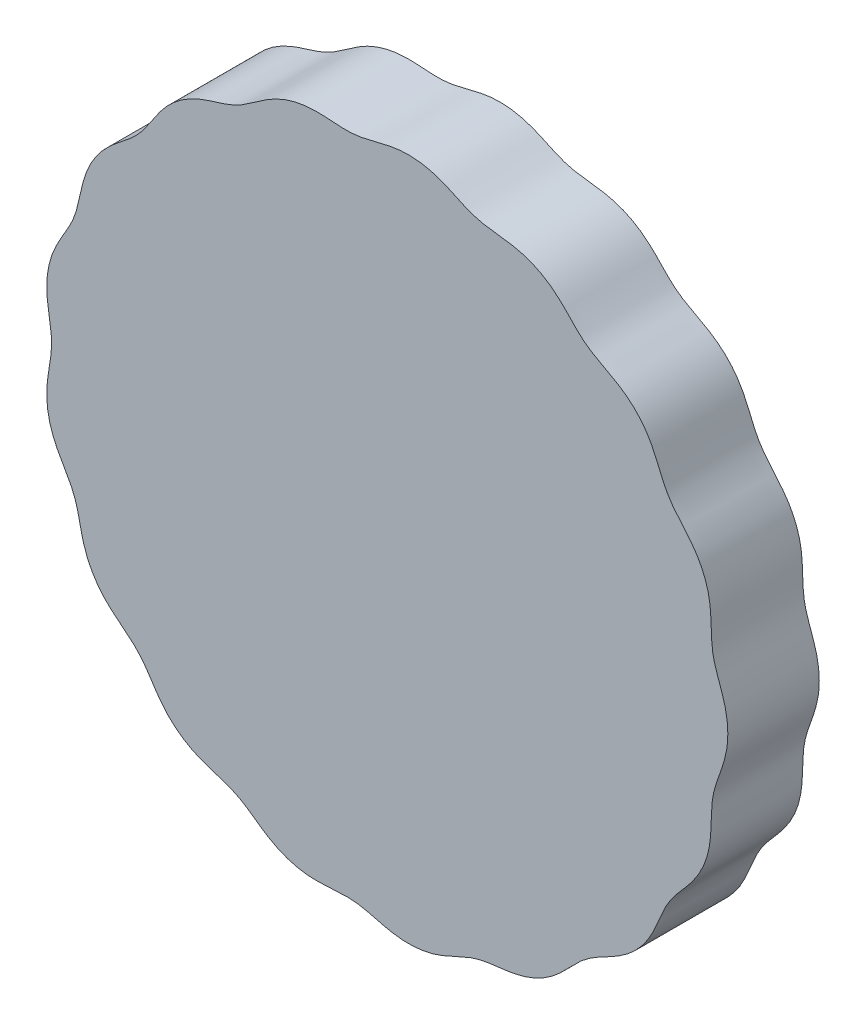
SolidWorks part; units mm, degrees
ref_plane "Front Plane" through (0, 0, 0) normal (0, 0, 1) x (1, 0, 0)
ref_plane "Top Plane" through (0, 0, 0) normal (0, 1, 0) x (1, 0, 0)
ref_plane "Right Plane" through (0, 0, 0) normal (1, 0, 0) x (0, 0, -1)
curve "Curve2"
  spline degree 3 poles (37.4783, -0.2259, 0) (37.4808, 0, 0) (37.4783, 0.2259, 0) (37.4707, 0.4525, 0) (37.4578, 0.6808, 0) (37.4392, 0.9112, 0) (37.4148, 1.1439, 0) (37.3841, 1.3792, 0) (37.347, 1.6168, 0) (37.3035, 1.8564, 0) (37.2536, 2.0975, 0) (37.1976, 2.3394, 0) (37.136, 2.5815, 0) (37.0693, 2.8232, 0) (36.9981, 3.0638, 0) (36.9231, 3.303, 0) (36.8453, 3.5401, 0) (36.7653, 3.7749, 0) (36.6841, 4.007, 0) (36.6025, 4.2364, 0) (36.5213, 4.463, 0) (36.4413, 4.6868, 0) (36.3632, 4.9078, 0) (36.2878, 5.1264, 0) (36.2156, 5.3428, 0) (36.1471, 5.5573, 0) (36.0829, 5.7702, 0) (36.0234, 5.9821, 0) (35.9687, 6.1933, 0) (35.9191, 6.4044, 0) (35.8748, 6.6158, 0) (35.8356, 6.8279, 0) (35.8015, 7.0413, 0) (35.7723, 7.2564, 0) (35.7478, 7.4735, 0) (35.7275, 7.693, 0) (35.7111, 7.9153, 0) (35.6979, 8.1406, 0) (35.6875, 8.369, 0) (35.6793, 8.6006, 0) (35.6724, 8.8355, 0) (35.6662, 9.0736, 0) (35.6601, 9.3147, 0) (35.6531, 9.5586, 0) (35.6447, 9.8048, 0) (35.634, 10.0529, 0) (35.6203, 10.3023, 0) (35.6031, 10.5525, 0) (35.5818, 10.8025, 0) (35.5559, 11.0518, 0) (35.525, 11.2995, 0) (35.4889, 11.5448, 0) (35.4474, 11.787, 0) (35.4005, 12.0254, 0) (35.3483, 12.2596, 0) (35.291, 12.4893, 0) (35.2289, 12.7144, 0) (35.1622, 12.9351, 0) (35.091, 13.152, 0) (35.0154, 13.3656, 0) (34.9354, 13.5768, 0) (34.8506, 13.7862, 0) (34.7607, 13.9947, 0) (34.6651, 14.2029, 0) (34.5635, 14.411, 0) (34.4554, 14.6192, 0) (34.3406, 14.8275, 0) (34.219, 15.0357, 0) (34.0907, 15.2432, 0) (33.956, 15.4497, 0) (33.8155, 15.6548, 0) (33.6697, 15.8579, 0) (33.5194, 16.0587, 0) (33.3655, 16.257, 0) (33.2088, 16.4524, 0) (33.0503, 16.6448, 0) (32.8908, 16.8344, 0) (32.7313, 17.021, 0) (32.5725, 17.205, 0) (32.4153, 17.3865, 0) (32.2603, 17.5659, 0) (32.1082, 17.7436, 0) (31.9595, 17.9199, 0) (31.8147, 18.0955, 0) (31.6742, 18.2708, 0) (31.5382, 18.4462, 0) (31.407, 18.6225, 0) (31.2806, 18.8, 0) (31.1589, 18.9792, 0) (31.042, 19.1607, 0) (30.9296, 19.3449, 0) (30.8215, 19.5321, 0) (30.7173, 19.7227, 0) (30.6165, 19.9169, 0) (30.5188, 20.115, 0) (30.4236, 20.3171, 0) (30.3303, 20.5231, 0) (30.2383, 20.733, 0) (30.1469, 20.9466, 0) (30.0556, 21.1638, 0) (29.9637, 21.3841, 0) (29.8706, 21.6072, 0) (29.7757, 21.8324, 0) (29.6784, 22.0591, 0) (29.5782, 22.2867, 0) (29.4748, 22.5143, 0) (29.3678, 22.7411, 0) (29.2569, 22.9663, 0) (29.1419, 23.1889, 0) (29.0229, 23.408, 0) (28.8999, 23.6228, 0) (28.7731, 23.8327, 0) (28.6426, 24.0371, 0) (28.5088, 24.2356, 0) (28.3719, 24.428, 0) (28.2321, 24.6144, 0) (28.0897, 24.7952, 0) (27.9445, 24.9709, 0) (27.7963, 25.142, 0) (27.6448, 25.3093, 0) (27.4893, 25.4735, 0) (27.3293, 25.635, 0) (27.164, 25.7942, 0) (26.9931, 25.9512, 0) (26.816, 26.1059, 0) (26.6325, 26.2582, 0) (26.4429, 26.4079, 0) (26.2472, 26.5545, 0) (26.0461, 26.6978, 0) (25.8402, 26.8376, 0) (25.6302, 26.9737, 0) (25.417, 27.106, 0) (25.2016, 27.2346, 0) (24.9847, 27.3596, 0) (24.7673, 27.4812, 0) (24.5503, 27.5998, 0) (24.3343, 27.7158, 0) (24.1202, 27.8297, 0) (23.9084, 27.9419, 0) (23.6997, 28.053, 0) (23.4943, 28.1637, 0) (23.2926, 28.2745, 0) (23.0949, 28.3861, 0) (22.9013, 28.4991, 0) (22.7119, 28.614, 0) (22.5265, 28.7314, 0) (22.3452, 28.8518, 0) (22.1677, 28.9756, 0) (21.9937, 29.1033, 0) (21.8229, 29.2352, 0) (21.6549, 29.3715, 0) (21.4892, 29.5124, 0) (21.3254, 29.658, 0) (21.163, 29.8082, 0) (21.0013, 29.963, 0) (20.8399, 30.1221, 0) (20.6781, 30.2853, 0) (20.5156, 30.4522, 0) (20.3517, 30.6222, 0) (20.1861, 30.7949, 0) (20.0183, 30.9695, 0) (19.848, 31.1454, 0) (19.6748, 31.3217, 0) (19.4987, 31.4976, 0) (19.3195, 31.6722, 0) (19.1372, 31.8446, 0) (18.9519, 32.0138, 0) (18.7639, 32.1791, 0) (18.5734, 32.3395, 0) (18.3807, 32.4944, 0) (18.1863, 32.6432, 0) (17.9906, 32.7855, 0) (17.794, 32.921, 0) (17.5967, 33.0498, 0) (17.399, 33.172, 0) (17.2008, 33.2881, 0) (17.0018, 33.3984, 0) (16.8015, 33.5036, 0) (16.5993, 33.6041, 0) (16.3945, 33.7003, 0) (16.1863, 33.7924, 0) (15.974, 33.8804, 0) (15.757, 33.9642, 0) (15.5351, 34.0438, 0) (15.3081, 34.1187, 0) (15.0764, 34.1889, 0) (14.8403, 34.2541, 0) (14.6003, 34.3142, 0) (14.3573, 34.3692, 0) (14.112, 34.4194, 0) (13.8652, 34.465, 0) (13.6178, 34.5064, 0) (13.3705, 34.544, 0) (13.1241, 34.5783, 0) (12.8791, 34.6101, 0) (12.6363, 34.64, 0) (12.3959, 34.6686, 0) (12.1585, 34.6967, 0) (11.9243, 34.725, 0) (11.6934, 34.7542, 0) (11.4659, 34.7851, 0) (11.2418, 34.8181, 0) (11.021, 34.8541, 0) (10.8034, 34.8934, 0) (10.5887, 34.9367, 0) (10.3766, 34.9842, 0) (10.1667, 35.0364, 0) (9.9586, 35.0935, 0) (9.7519, 35.1557, 0) (9.5461, 35.223, 0) (9.3408, 35.2955, 0) (9.1354, 35.3729, 0) (8.9295, 35.4551, 0) (8.7226, 35.5418, 0) (8.5143, 35.6326, 0) (8.3042, 35.7269, 0) (8.092, 35.8243, 0) (7.8773, 35.924, 0) (7.6601, 36.0254, 0) (7.44, 36.1277, 0) (7.2171, 36.2302, 0) (6.9915, 36.3318, 0) (6.7633, 36.4319, 0) (6.5327, 36.5295, 0) (6.3002, 36.6237, 0) (6.066, 36.7138, 0) (5.8308, 36.7991, 0) (5.5952, 36.8788, 0) (5.3596, 36.9526, 0) (5.1248, 37.0199, 0) (4.8911, 37.0807, 0) (4.6591, 37.1349, 0) (4.429, 37.1826, 0) (4.2008, 37.2241, 0) (3.9743, 37.2597, 0) (3.7491, 37.2898, 0) (3.5244, 37.3146, 0) (3.2995, 37.3344, 0) (3.0735, 37.3492, 0) (2.8457, 37.3589, 0) (2.6154, 37.3634, 0) (2.3823, 37.3622, 0) (2.1461, 37.3551, 0) (1.9069, 37.3419, 0) (1.665, 37.3225, 0) (1.4209, 37.2969, 0) (1.1753, 37.2652, 0) (0.9286, 37.2278, 0) (0.6818, 37.1851, 0) (0.4353, 37.1377, 0) (0.1899, 37.0862, 0) (-0.054, 37.0314, 0) (-0.2958, 36.974, 0) (-0.5352, 36.9149, 0) (-0.772, 36.8549, 0) (-1.0059, 36.7949, 0) (-1.237, 36.7355, 0) (-1.4651, 36.6776, 0) (-1.6905, 36.6218, 0) (-1.9134, 36.569, 0) (-2.1339, 36.5195, 0) (-2.3524, 36.474, 0) (-2.5692, 36.4329, 0) (-2.7849, 36.3965, 0) (-2.9998, 36.3651, 0) (-3.2143, 36.3389, 0) (-3.4291, 36.3179, 0) (-3.6444, 36.3021, 0) (-3.8608, 36.2914, 0) (-4.0788, 36.2857, 0) (-4.2986, 36.2845, 0) (-4.5207, 36.2874, 0) (-4.7454, 36.2942, 0) (-4.9729, 36.3041, 0) (-5.2035, 36.3165, 0) (-5.4371, 36.331, 0) (-5.6738, 36.3466, 0) (-5.9136, 36.3627, 0) (-6.1563, 36.3785, 0) (-6.4015, 36.3932, 0) (-6.649, 36.4062, 0) (-6.8982, 36.4165, 0) (-7.1486, 36.4236, 0) (-7.3996, 36.4267, 0) (-7.6504, 36.4253, 0) (-7.9003, 36.4189, 0) (-8.1485, 36.4072, 0) (-8.3943, 36.3899, 0) (-8.637, 36.3669, 0) (-8.8762, 36.3382, 0) (-9.1114, 36.3039, 0) (-9.3424, 36.2644, 0) (-9.5695, 36.2197, 0) (-9.793, 36.1703, 0) (-10.0134, 36.1161, 0) (-10.2316, 36.0573, 0) (-10.4482, 35.9936, 0) (-10.6642, 35.9249, 0) (-10.8802, 35.8507, 0) (-11.0966, 35.7705, 0) (-11.3137, 35.684, 0) (-11.5316, 35.5909, 0) (-11.7499, 35.491, 0) (-11.9684, 35.3844, 0) (-12.1867, 35.2712, 0) (-12.4042, 35.1519, 0) (-12.6204, 35.027, 0) (-12.8348, 34.8971, 0) (-13.0471, 34.7632, 0) (-13.2569, 34.626, 0) (-13.464, 34.4865, 0) (-13.6682, 34.3454, 0) (-13.8697, 34.2038, 0) (-14.0683, 34.0624, 0) (-14.2643, 33.9221, 0) (-14.4578, 33.7837, 0) (-14.6493, 33.6478, 0) (-14.8391, 33.515, 0) (-15.0276, 33.3859, 0) (-15.2152, 33.2608, 0) (-15.4025, 33.1403, 0) (-15.5899, 33.0244, 0) (-15.778, 32.9135, 0) (-15.9673, 32.8074, 0) (-16.1582, 32.7063, 0) (-16.3513, 32.61, 0) (-16.5469, 32.5183, 0) (-16.7454, 32.4309, 0) (-16.9471, 32.3475, 0) (-17.1523, 32.2675, 0) (-17.3611, 32.1906, 0) (-17.5737, 32.116, 0) (-17.7901, 32.0434, 0) (-18.0102, 31.9719, 0) (-18.2339, 31.901, 0) (-18.4609, 31.83, 0) (-18.6908, 31.7582, 0) (-18.9232, 31.685, 0) (-19.1575, 31.6097, 0) (-19.3931, 31.5319, 0) (-19.6292, 31.4509, 0) (-19.8652, 31.3664, 0) (-20.1001, 31.2779, 0) (-20.333, 31.1853, 0) (-20.5632, 31.0883, 0) (-20.7897, 30.9869, 0) (-21.0118, 30.8812, 0) (-21.229, 30.7714, 0) (-21.4406, 30.6575, 0) (-21.6465, 30.54, 0) (-21.8467, 30.419, 0) (-22.0414, 30.2948, 0) (-22.231, 30.1674, 0) (-22.4163, 30.0367, 0) (-22.5978, 29.9023, 0) (-22.7764, 29.764, 0) (-22.9526, 29.621, 0) (-23.1268, 29.4728, 0) (-23.2994, 29.3188, 0) (-23.4703, 29.1586, 0) (-23.6395, 28.992, 0) (-23.8066, 28.8188, 0) (-23.9715, 28.6393, 0) (-24.1336, 28.4539, 0) (-24.2927, 28.2632, 0) (-24.4486, 28.0679, 0) (-24.601, 27.8688, 0) (-24.75, 27.6668, 0) (-24.8955, 27.4628, 0) (-25.0376, 27.2577, 0) (-25.1766, 27.0524, 0) (-25.3127, 26.8478, 0) (-25.4465, 26.6445, 0) (-25.5782, 26.4433, 0) (-25.7085, 26.2448, 0) (-25.8378, 26.0494, 0) (-25.9668, 25.8577, 0) (-26.096, 25.67, 0) (-26.226, 25.4864, 0) (-26.3573, 25.307, 0) (-26.4907, 25.1321, 0) (-26.6264, 24.9614, 0) (-26.7652, 24.7949, 0) (-26.9073, 24.6323, 0) (-27.0533, 24.4734, 0) (-27.2032, 24.3178, 0) (-27.3575, 24.1651, 0) (-27.5163, 24.0148, 0) (-27.6795, 23.8664, 0) (-27.8473, 23.7194, 0) (-28.0193, 23.5732, 0) (-28.1956, 23.4273, 0) (-28.3757, 23.281, 0) (-28.5592, 23.1339, 0) (-28.7457, 22.9854, 0) (-28.9345, 22.8351, 0) (-29.125, 22.6824, 0) (-29.3164, 22.5271, 0) (-29.5079, 22.3689, 0) (-29.6987, 22.2075, 0) (-29.8878, 22.0429, 0) (-30.0743, 21.875, 0) (-30.2574, 21.7039, 0) (-30.4362, 21.5298, 0) (-30.6098, 21.353, 0) (-30.7777, 21.1738, 0) (-30.9394, 20.9925, 0) (-31.0944, 20.8097, 0) (-31.2428, 20.6255, 0) (-31.3846, 20.4402, 0) (-31.5202, 20.2539, 0) (-31.6501, 20.0663, 0) (-31.7747, 19.8772, 0) (-31.8947, 19.6859, 0) (-32.0105, 19.4918, 0) (-32.1225, 19.2942, 0) (-32.2308, 19.0922, 0) (-32.3354, 18.8854, 0) (-32.4363, 18.6734, 0) (-32.5331, 18.4559, 0) (-32.6256, 18.2331, 0) (-32.7136, 18.0054, 0) (-32.797, 17.7732, 0) (-32.8757, 17.5373, 0) (-32.9496, 17.2983, 0) (-33.0191, 17.0573, 0) (-33.0843, 16.815, 0) (-33.1456, 16.5722, 0) (-33.2035, 16.3297, 0) (-33.2584, 16.0883, 0) (-33.3111, 15.8486, 0) (-33.3622, 15.6112, 0) (-33.4122, 15.3765, 0) (-33.462, 15.1449, 0) (-33.5121, 14.9167, 0) (-33.5634, 14.6919, 0) (-33.6163, 14.4708, 0) (-33.6717, 14.2533, 0) (-33.73, 14.0392, 0) (-33.7917, 13.8285, 0) (-33.8574, 13.6208, 0) (-33.9274, 13.4159, 0) (-34.0021, 13.2133, 0) (-34.0816, 13.0127, 0) (-34.1662, 12.8137, 0) (-34.2557, 12.6157, 0) (-34.3503, 12.4183, 0) (-34.4498, 12.2209, 0) (-34.5539, 12.0231, 0) (-34.6623, 11.8244, 0) (-34.7746, 11.6244, 0) (-34.8902, 11.4227, 0) (-35.0087, 11.2188, 0) (-35.1292, 11.0125, 0) (-35.2511, 10.8037, 0) (-35.3737, 10.592, 0) (-35.496, 10.3776, 0) (-35.6171, 10.1604, 0) (-35.7363, 9.9405, 0) (-35.8526, 9.7183, 0) (-35.9652, 9.494, 0) (-36.0733, 9.268, 0) (-36.1761, 9.041, 0) (-36.2731, 8.8133, 0) (-36.3637, 8.5856, 0) (-36.4478, 8.3583, 0) (-36.5252, 8.132, 0) (-36.5958, 7.9069, 0) (-36.66, 7.6831, 0) (-36.7181, 7.4605, 0) (-36.7704, 7.2389, 0) (-36.8174, 7.0175, 0) (-36.8593, 6.7956, 0) (-36.8963, 6.5725, 0) (-36.9285, 6.3474, 0) (-36.9556, 6.1194, 0) (-36.9776, 5.8882, 0) (-36.994, 5.6534, 0) (-37.0047, 5.415, 0) (-37.0094, 5.1733, 0) (-37.0082, 4.9286, 0) (-37.001, 4.6816, 0) (-36.9882, 4.433, 0) (-36.9699, 4.1834, 0) (-36.9468, 3.9335, 0) (-36.9193, 3.6841, 0) (-36.8882, 3.4358, 0) (-36.8541, 3.1891, 0) (-36.8178, 2.9446, 0) (-36.7802, 2.7025, 0) (-36.7419, 2.4632, 0) (-36.7039, 2.2268, 0) (-36.6669, 1.9934, 0) (-36.6316, 1.7629, 0) (-36.5986, 1.5354, 0) (-36.5687, 1.3105, 0) (-36.5424, 1.0881, 0) (-36.5202, 0.8678, 0) (-36.5025, 0.6492, 0) (-36.4896, 0.4321, 0) (-36.4818, 0.2158, 0) (-36.4791, 0, 0) (-36.4818, -0.2158, 0) (-36.4896, -0.4321, 0) (-36.5025, -0.6492, 0) (-36.5202, -0.8678, 0) (-36.5424, -1.0881, 0) (-36.5687, -1.3105, 0) (-36.5986, -1.5354, 0) (-36.6316, -1.7629, 0) (-36.6669, -1.9934, 0) (-36.7039, -2.2268, 0) (-36.7419, -2.4632, 0) (-36.7802, -2.7025, 0) (-36.8178, -2.9446, 0) (-36.8541, -3.1891, 0) (-36.8882, -3.4358, 0) (-36.9193, -3.6841, 0) (-36.9468, -3.9335, 0) (-36.9699, -4.1834, 0) (-36.9882, -4.433, 0) (-37.001, -4.6816, 0) (-37.0082, -4.9286, 0) (-37.0094, -5.1733, 0) (-37.0047, -5.415, 0) (-36.994, -5.6534, 0) (-36.9776, -5.8882, 0) (-36.9556, -6.1194, 0) (-36.9285, -6.3474, 0) (-36.8963, -6.5725, 0) (-36.8593, -6.7956, 0) (-36.8174, -7.0175, 0) (-36.7704, -7.2389, 0) (-36.7181, -7.4605, 0) (-36.66, -7.6831, 0) (-36.5958, -7.9069, 0) (-36.5252, -8.132, 0) (-36.4478, -8.3583, 0) (-36.3637, -8.5856, 0) (-36.2731, -8.8133, 0) (-36.1761, -9.041, 0) (-36.0733, -9.268, 0) (-35.9652, -9.494, 0) (-35.8526, -9.7183, 0) (-35.7363, -9.9405, 0) (-35.6171, -10.1604, 0) (-35.496, -10.3776, 0) (-35.3737, -10.592, 0) (-35.2511, -10.8037, 0) (-35.1292, -11.0125, 0) (-35.0087, -11.2188, 0) (-34.8902, -11.4227, 0) (-34.7746, -11.6244, 0) (-34.6623, -11.8244, 0) (-34.5539, -12.0231, 0) (-34.4498, -12.2209, 0) (-34.3503, -12.4183, 0) (-34.2557, -12.6157, 0) (-34.1662, -12.8137, 0) (-34.0816, -13.0127, 0) (-34.0021, -13.2133, 0) (-33.9274, -13.4159, 0) (-33.8574, -13.6208, 0) (-33.7917, -13.8285, 0) (-33.73, -14.0392, 0) (-33.6717, -14.2533, 0) (-33.6163, -14.4708, 0) (-33.5634, -14.6919, 0) (-33.5121, -14.9167, 0) (-33.462, -15.1449, 0) (-33.4122, -15.3765, 0) (-33.3622, -15.6112, 0) (-33.3111, -15.8486, 0) (-33.2584, -16.0883, 0) (-33.2035, -16.3297, 0) (-33.1456, -16.5722, 0) (-33.0843, -16.815, 0) (-33.0191, -17.0573, 0) (-32.9496, -17.2983, 0) (-32.8757, -17.5373, 0) (-32.797, -17.7732, 0) (-32.7136, -18.0054, 0) (-32.6256, -18.2331, 0) (-32.5331, -18.4559, 0) (-32.4363, -18.6734, 0) (-32.3354, -18.8854, 0) (-32.2308, -19.0922, 0) (-32.1225, -19.2942, 0) (-32.0105, -19.4918, 0) (-31.8947, -19.6859, 0) (-31.7747, -19.8772, 0) (-31.6501, -20.0663, 0) (-31.5202, -20.2539, 0) (-31.3846, -20.4402, 0) (-31.2428, -20.6255, 0) (-31.0944, -20.8097, 0) (-30.9394, -20.9925, 0) (-30.7777, -21.1738, 0) (-30.6098, -21.353, 0) (-30.4362, -21.5298, 0) (-30.2574, -21.7039, 0) (-30.0743, -21.875, 0) (-29.8878, -22.0429, 0) (-29.6987, -22.2075, 0) (-29.5079, -22.3689, 0) (-29.3164, -22.5271, 0) (-29.125, -22.6824, 0) (-28.9345, -22.8351, 0) (-28.7457, -22.9854, 0) (-28.5592, -23.1339, 0) (-28.3757, -23.281, 0) (-28.1956, -23.4273, 0) (-28.0193, -23.5732, 0) (-27.8473, -23.7194, 0) (-27.6795, -23.8664, 0) (-27.5163, -24.0148, 0) (-27.3575, -24.1651, 0) (-27.2032, -24.3178, 0) (-27.0533, -24.4734, 0) (-26.9073, -24.6323, 0) (-26.7652, -24.7949, 0) (-26.6264, -24.9614, 0) (-26.4907, -25.1321, 0) (-26.3573, -25.307, 0) (-26.226, -25.4864, 0) (-26.096, -25.67, 0) (-25.9668, -25.8577, 0) (-25.8378, -26.0494, 0) (-25.7085, -26.2448, 0) (-25.5782, -26.4433, 0) (-25.4465, -26.6445, 0) (-25.3127, -26.8478, 0) (-25.1766, -27.0524, 0) (-25.0376, -27.2577, 0) (-24.8955, -27.4628, 0) (-24.75, -27.6668, 0) (-24.601, -27.8688, 0) (-24.4486, -28.0679, 0) (-24.2927, -28.2632, 0) (-24.1336, -28.4539, 0) (-23.9715, -28.6393, 0) (-23.8066, -28.8188, 0) (-23.6395, -28.992, 0) (-23.4703, -29.1586, 0) (-23.2994, -29.3188, 0) (-23.1268, -29.4728, 0) (-22.9526, -29.621, 0) (-22.7764, -29.764, 0) (-22.5978, -29.9023, 0) (-22.4163, -30.0367, 0) (-22.231, -30.1674, 0) (-22.0414, -30.2948, 0) (-21.8467, -30.419, 0) (-21.6465, -30.54, 0) (-21.4406, -30.6575, 0) (-21.229, -30.7714, 0) (-21.0118, -30.8812, 0) (-20.7897, -30.9869, 0) (-20.5632, -31.0883, 0) (-20.333, -31.1853, 0) (-20.1001, -31.2779, 0) (-19.8652, -31.3664, 0) (-19.6292, -31.4509, 0) (-19.3931, -31.5319, 0) (-19.1575, -31.6097, 0) (-18.9232, -31.685, 0) (-18.6908, -31.7582, 0) (-18.4609, -31.83, 0) (-18.2339, -31.901, 0) (-18.0102, -31.9719, 0) (-17.7901, -32.0434, 0) (-17.5737, -32.116, 0) (-17.3611, -32.1906, 0) (-17.1523, -32.2675, 0) (-16.9471, -32.3475, 0) (-16.7454, -32.4309, 0) (-16.5469, -32.5183, 0) (-16.3513, -32.61, 0) (-16.1582, -32.7063, 0) (-15.9673, -32.8074, 0) (-15.778, -32.9135, 0) (-15.5899, -33.0244, 0) (-15.4025, -33.1403, 0) (-15.2152, -33.2608, 0) (-15.0276, -33.3859, 0) (-14.8391, -33.515, 0) (-14.6493, -33.6478, 0) (-14.4578, -33.7837, 0) (-14.2643, -33.9221, 0) (-14.0683, -34.0624, 0) (-13.8697, -34.2038, 0) (-13.6682, -34.3454, 0) (-13.464, -34.4865, 0) (-13.2569, -34.626, 0) (-13.0471, -34.7632, 0) (-12.8348, -34.8971, 0) (-12.6204, -35.027, 0) (-12.4042, -35.1519, 0) (-12.1867, -35.2712, 0) (-11.9684, -35.3844, 0) (-11.7499, -35.491, 0) (-11.5316, -35.5909, 0) (-11.3137, -35.684, 0) (-11.0966, -35.7705, 0) (-10.8802, -35.8507, 0) (-10.6642, -35.9249, 0) (-10.4482, -35.9936, 0) (-10.2316, -36.0573, 0) (-10.0134, -36.1161, 0) (-9.793, -36.1703, 0) (-9.5695, -36.2197, 0) (-9.3424, -36.2644, 0) (-9.1114, -36.3039, 0) (-8.8762, -36.3382, 0) (-8.637, -36.3669, 0) (-8.3943, -36.3899, 0) (-8.1485, -36.4072, 0) (-7.9003, -36.4189, 0) (-7.6504, -36.4253, 0) (-7.3996, -36.4267, 0) (-7.1486, -36.4236, 0) (-6.8982, -36.4165, 0) (-6.649, -36.4062, 0) (-6.4015, -36.3932, 0) (-6.1563, -36.3785, 0) (-5.9136, -36.3627, 0) (-5.6738, -36.3466, 0) (-5.4371, -36.331, 0) (-5.2035, -36.3165, 0) (-4.9729, -36.3041, 0) (-4.7454, -36.2942, 0) (-4.5207, -36.2874, 0) (-4.2986, -36.2845, 0) (-4.0788, -36.2857, 0) (-3.8608, -36.2914, 0) (-3.6444, -36.3021, 0) (-3.4291, -36.3179, 0) (-3.2143, -36.3389, 0) (-2.9998, -36.3651, 0) (-2.7849, -36.3965, 0) (-2.5692, -36.4329, 0) (-2.3524, -36.474, 0) (-2.1339, -36.5195, 0) (-1.9134, -36.569, 0) (-1.6905, -36.6218, 0) (-1.4651, -36.6776, 0) (-1.237, -36.7355, 0) (-1.0059, -36.7949, 0) (-0.772, -36.8549, 0) (-0.5352, -36.9149, 0) (-0.2958, -36.974, 0) (-0.054, -37.0314, 0) (0.1899, -37.0862, 0) (0.4353, -37.1377, 0) (0.6818, -37.1851, 0) (0.9286, -37.2278, 0) (1.1753, -37.2652, 0) (1.4209, -37.2969, 0) (1.665, -37.3225, 0) (1.9069, -37.3419, 0) (2.1461, -37.3551, 0) (2.3823, -37.3622, 0) (2.6154, -37.3634, 0) (2.8457, -37.3589, 0) (3.0735, -37.3492, 0) (3.2995, -37.3344, 0) (3.5244, -37.3146, 0) (3.7491, -37.2898, 0) (3.9743, -37.2597, 0) (4.2008, -37.2241, 0) (4.429, -37.1826, 0) (4.6591, -37.1349, 0) (4.8911, -37.0807, 0) (5.1248, -37.0199, 0) (5.3596, -36.9526, 0) (5.5952, -36.8788, 0) (5.8308, -36.7991, 0) (6.066, -36.7138, 0) (6.3002, -36.6237, 0) (6.5327, -36.5295, 0) (6.7633, -36.4319, 0) (6.9915, -36.3318, 0) (7.2171, -36.2302, 0) (7.44, -36.1277, 0) (7.6601, -36.0254, 0) (7.8773, -35.924, 0) (8.092, -35.8243, 0) (8.3042, -35.7269, 0) (8.5143, -35.6326, 0) (8.7226, -35.5418, 0) (8.9295, -35.4551, 0) (9.1354, -35.3729, 0) (9.3408, -35.2955, 0) (9.5461, -35.223, 0) (9.7519, -35.1557, 0) (9.9586, -35.0935, 0) (10.1667, -35.0364, 0) (10.3766, -34.9842, 0) (10.5887, -34.9367, 0) (10.8034, -34.8934, 0) (11.021, -34.8541, 0) (11.2418, -34.8181, 0) (11.4659, -34.7851, 0) (11.6934, -34.7542, 0) (11.9243, -34.725, 0) (12.1585, -34.6967, 0) (12.3959, -34.6686, 0) (12.6363, -34.64, 0) (12.8791, -34.6101, 0) (13.1241, -34.5783, 0) (13.3705, -34.544, 0) (13.6178, -34.5064, 0) (13.8652, -34.465, 0) (14.112, -34.4194, 0) (14.3573, -34.3692, 0) (14.6003, -34.3142, 0) (14.8403, -34.2541, 0) (15.0764, -34.1889, 0) (15.3081, -34.1187, 0) (15.5351, -34.0438, 0) (15.757, -33.9642, 0) (15.974, -33.8804, 0) (16.1863, -33.7924, 0) (16.3945, -33.7003, 0) (16.5993, -33.6041, 0) (16.8015, -33.5036, 0) (17.0018, -33.3984, 0) (17.2008, -33.2881, 0) (17.399, -33.172, 0) (17.5967, -33.0498, 0) (17.794, -32.921, 0) (17.9906, -32.7855, 0) (18.1863, -32.6432, 0) (18.3807, -32.4944, 0) (18.5734, -32.3395, 0) (18.7639, -32.1791, 0) (18.9519, -32.0138, 0) (19.1372, -31.8446, 0) (19.3195, -31.6722, 0) (19.4987, -31.4976, 0) (19.6748, -31.3217, 0) (19.848, -31.1454, 0) (20.0183, -30.9695, 0) (20.1861, -30.7949, 0) (20.3517, -30.6222, 0) (20.5156, -30.4522, 0) (20.6781, -30.2853, 0) (20.8399, -30.1221, 0) (21.0013, -29.963, 0) (21.163, -29.8082, 0) (21.3254, -29.658, 0) (21.4892, -29.5124, 0) (21.6549, -29.3715, 0) (21.8229, -29.2352, 0) (21.9937, -29.1033, 0) (22.1677, -28.9756, 0) (22.3452, -28.8518, 0) (22.5265, -28.7314, 0) (22.7119, -28.614, 0) (22.9013, -28.4991, 0) (23.0949, -28.3861, 0) (23.2926, -28.2745, 0) (23.4943, -28.1637, 0) (23.6997, -28.053, 0) (23.9084, -27.9419, 0) (24.1202, -27.8297, 0) (24.3343, -27.7158, 0) (24.5503, -27.5998, 0) (24.7673, -27.4812, 0) (24.9847, -27.3596, 0) (25.2016, -27.2346, 0) (25.417, -27.106, 0) (25.6302, -26.9737, 0) (25.8402, -26.8376, 0) (26.0461, -26.6978, 0) (26.2472, -26.5545, 0) (26.4429, -26.4079, 0) (26.6325, -26.2582, 0) (26.816, -26.1059, 0) (26.9931, -25.9512, 0) (27.164, -25.7942, 0) (27.3293, -25.635, 0) (27.4893, -25.4735, 0) (27.6448, -25.3093, 0) (27.7963, -25.142, 0) (27.9445, -24.9709, 0) (28.0897, -24.7952, 0) (28.2321, -24.6144, 0) (28.3719, -24.428, 0) (28.5088, -24.2356, 0) (28.6426, -24.0371, 0) (28.7731, -23.8327, 0) (28.8999, -23.6228, 0) (29.0229, -23.408, 0) (29.1419, -23.1889, 0) (29.2569, -22.9663, 0) (29.3678, -22.7411, 0) (29.4748, -22.5143, 0) (29.5782, -22.2867, 0) (29.6784, -22.0591, 0) (29.7757, -21.8324, 0) (29.8706, -21.6072, 0) (29.9637, -21.3841, 0) (30.0556, -21.1638, 0) (30.1469, -20.9466, 0) (30.2383, -20.733, 0) (30.3303, -20.5231, 0) (30.4236, -20.3171, 0) (30.5188, -20.115, 0) (30.6165, -19.9169, 0) (30.7173, -19.7227, 0) (30.8215, -19.5321, 0) (30.9296, -19.3449, 0) (31.042, -19.1607, 0) (31.1589, -18.9792, 0) (31.2806, -18.8, 0) (31.407, -18.6225, 0) (31.5382, -18.4462, 0) (31.6742, -18.2708, 0) (31.8147, -18.0955, 0) (31.9595, -17.9199, 0) (32.1082, -17.7436, 0) (32.2603, -17.5659, 0) (32.4153, -17.3865, 0) (32.5725, -17.205, 0) (32.7313, -17.021, 0) (32.8908, -16.8344, 0) (33.0503, -16.6448, 0) (33.2088, -16.4524, 0) (33.3655, -16.257, 0) (33.5194, -16.0587, 0) (33.6697, -15.8579, 0) (33.8155, -15.6548, 0) (33.956, -15.4497, 0) (34.0907, -15.2432, 0) (34.219, -15.0357, 0) (34.3406, -14.8275, 0) (34.4554, -14.6192, 0) (34.5635, -14.411, 0) (34.6651, -14.2029, 0) (34.7607, -13.9947, 0) (34.8506, -13.7862, 0) (34.9354, -13.5768, 0) (35.0154, -13.3656, 0) (35.091, -13.152, 0) (35.1622, -12.9351, 0) (35.2289, -12.7144, 0) (35.291, -12.4893, 0) (35.3483, -12.2596, 0) (35.4005, -12.0254, 0) (35.4474, -11.787, 0) (35.4889, -11.5448, 0) (35.525, -11.2995, 0) (35.5559, -11.0518, 0) (35.5818, -10.8025, 0) (35.6031, -10.5525, 0) (35.6203, -10.3023, 0) (35.634, -10.0529, 0) (35.6447, -9.8048, 0) (35.6531, -9.5586, 0) (35.6601, -9.3147, 0) (35.6662, -9.0736, 0) (35.6724, -8.8355, 0) (35.6793, -8.6006, 0) (35.6875, -8.369, 0) (35.6979, -8.1406, 0) (35.7111, -7.9153, 0) (35.7275, -7.693, 0) (35.7478, -7.4735, 0) (35.7723, -7.2564, 0) (35.8015, -7.0413, 0) (35.8356, -6.8279, 0) (35.8748, -6.6158, 0) (35.9191, -6.4044, 0) (35.9687, -6.1933, 0) (36.0234, -5.9821, 0) (36.0829, -5.7702, 0) (36.1471, -5.5573, 0) (36.2156, -5.3428, 0) (36.2878, -5.1264, 0) (36.3632, -4.9078, 0) (36.4413, -4.6868, 0) (36.5213, -4.463, 0) (36.6025, -4.2364, 0) (36.6841, -4.007, 0) (36.7653, -3.7749, 0) (36.8453, -3.5401, 0) (36.9231, -3.303, 0) (36.9981, -3.0638, 0) (37.0693, -2.8232, 0) (37.136, -2.5815, 0) (37.1976, -2.3394, 0) (37.2536, -2.0975, 0) (37.3035, -1.8564, 0) (37.347, -1.6168, 0) (37.3841, -1.3792, 0) (37.4148, -1.1439, 0) (37.4392, -0.9112, 0) (37.4578, -0.6808, 0) (37.4707, -0.4525, 0) (37.4783, -0.2259, 0) (37.4808, 0, 0) (37.4783, 0.2259, 0) knots -0.002887 -0.001918 -0.000957 0 0.000957 0.001918 0.002887 0.003867 0.00486 0.005867 0.006888 0.007922 0.008967 0.010021 0.011082 0.012147 0.013213 0.014278 0.015338 0.016391 0.017435 0.018469 0.019491 0.020499 0.021494 0.022476 0.023443 0.024398 0.025342 0.026275 0.0272 0.02812 0.029035 0.02995 0.030866 0.031786 0.032712 0.033647 0.034593 0.03555 0.03652 0.037504 0.038501 0.039512 0.040536 0.041572 0.042618 0.043672 0.044733 0.045798 0.046864 0.047929 0.048989 0.050042 0.051085 0.052117 0.053135 0.054139 0.05513 0.056108 0.057075 0.058036 0.058992 0.05995 0.060912 0.061883 0.062865 0.063861 0.06487 0.065893 0.066929 0.067976 0.069032 0.070094 0.071159 0.072225 0.073289 0.074348 0.0754 0.076442 0.077474 0.078493 0.0795 0.080492 0.081471 0.082436 0.083389 0.084331 0.085262 0.086186 0.087105 0.08802 0.088935 0.089851 0.090772 0.0917 0.092637 0.093584 0.094544 0.095516 0.096502 0.097502 0.098515 0.099541 0.100579 0.101627 0.102683 0.103745 0.10481 0.105876 0.10694 0.107999 0.10905 0.110092 0.111121 0.112137 0.113139 0.114127 0.115103 0.116069 0.117028 0.117985 0.118943 0.119906 0.120879 0.121863 0.122861 0.123873 0.124898 0.125937 0.126985 0.128042 0.129105 0.130171 0.131236 0.1323 0.133357 0.134408 0.135449 0.136478 0.137495 0.138499 0.139489 0.140466 0.141429 0.14238 0.143319 0.14425 0.145172 0.14609 0.147005 0.14792 0.148837 0.149759 0.150688 0.151627 0.152576 0.153538 0.154513 0.155501 0.156503 0.157519 0.158547 0.159587 0.160636 0.161693 0.162756 0.163821 0.164887 0.165951 0.167008 0.168058 0.169098 0.170125 0.171138 0.172138 0.173123 0.174097 0.175062 0.17602 0.176977 0.177936 0.178901 0.179875 0.180862 0.181862 0.182877 0.183904 0.184944 0.185995 0.187053 0.188117 0.189182 0.190248 0.19131 0.192367 0.193416 0.194455 0.195482 0.196497 0.197499 0.198486 0.19946 0.200421 0.20137 0.202308 0.203236 0.204158 0.205075 0.20599 0.206905 0.207823 0.208746 0.209677 0.210617 0.211569 0.212532 0.21351 0.214501 0.215505 0.216523 0.217554 0.218595 0.219646 0.220704 0.221767 0.222833 0.223899 0.224961 0.226018 0.227066 0.228103 0.229128 0.230139 0.231136 0.23212 0.233092 0.234055 0.235013 0.235969 0.236929 0.237896 0.238872 0.239861 0.240864 0.24188 0.242911 0.243953 0.245005 0.246064 0.247128 0.248194 0.249259 0.250321 0.251376 0.252423 0.25346 0.254486 0.255498 0.256497 0.257483 0.258454 0.259413 0.26036 0.261296 0.262223 0.263144 0.26406 0.264975 0.26589 0.266809 0.267733 0.268666 0.269608 0.270561 0.271527 0.272507 0.2735 0.274507 0.275528 0.27656 0.277603 0.278656 0.279715 0.280779 0.281845 0.28291 0.283972 0.285027 0.286073 0.287109 0.288131 0.28914 0.290134 0.291116 0.292086 0.293048 0.294005 0.294962 0.295923 0.296891 0.297869 0.29886 0.299866 0.300885 0.301917 0.302961 0.304015 0.305075 0.30614 0.307206 0.30827 0.309331 0.310385 0.311431 0.312466 0.313489 0.314499 0.315496 0.316479 0.317448 0.318404 0.319349 0.320283 0.321209 0.322129 0.323045 0.32396 0.324876 0.325795 0.326721 0.327655 0.328599 0.329554 0.330523 0.331505 0.332501 0.33351 0.334533 0.335567 0.336612 0.337666 0.338726 0.33979 0.340856 0.341921 0.342982 0.344036 0.345081 0.346114 0.347134 0.34814 0.349132 0.350111 0.35108 0.35204 0.352997 0.353955 0.354916 0.355886 0.356867 0.35786 0.358868 0.35989 0.360924 0.36197 0.363025 0.364086 0.365151 0.366217 0.367281 0.368341 0.369394 0.370438 0.371471 0.372492 0.3735 0.374494 0.375474 0.376441 0.377395 0.378338 0.379271 0.380196 0.381115 0.38203 0.382945 0.383861 0.384781 0.385708 0.386644 0.38759 0.388548 0.389519 0.390503 0.391501 0.392513 0.393538 0.394574 0.395621 0.396676 0.397737 0.398802 0.399868 0.400932 0.401992 0.403045 0.404087 0.405118 0.406136 0.407139 0.408129 0.409106 0.410073 0.411033 0.41199 0.412947 0.41391 0.414882 0.415865 0.416861 0.417871 0.418895 0.419931 0.420979 0.422035 0.423098 0.424163 0.425229 0.426292 0.427351 0.428402 0.429444 0.430475 0.431494 0.4325 0.433491 0.434469 0.435434 0.436386 0.437327 0.438258 0.439182 0.4401 0.441015 0.44193 0.442847 0.443768 0.444696 0.445634 0.446582 0.447542 0.448515 0.449502 0.450502 0.451517 0.452543 0.453582 0.45463 0.455686 0.456748 0.457814 0.45888 0.459943 0.461002 0.462053 0.463094 0.464122 0.465137 0.466138 0.467126 0.468101 0.469066 0.470026 0.470982 0.47194 0.472904 0.473878 0.474863 0.475861 0.476874 0.4779 0.478939 0.479988 0.481046 0.482109 0.483175 0.48424 0.485303 0.486361 0.48741 0.488451 0.48948 0.490496 0.491499 0.492488 0.493464 0.494426 0.495376 0.496315 0.497245 0.498168 0.499085 0.5 0.500915 0.501832 0.502755 0.503685 0.504624 0.505574 0.506536 0.507512 0.508501 0.509504 0.51052 0.511549 0.51259 0.513639 0.514697 0.51576 0.516825 0.517891 0.518954 0.520012 0.521061 0.5221 0.523126 0.524139 0.525137 0.526122 0.527096 0.52806 0.529018 0.529974 0.530934 0.531899 0.532874 0.533862 0.534863 0.535878 0.536906 0.537947 0.538998 0.540057 0.54112 0.542186 0.543252 0.544314 0.54537 0.546418 0.547457 0.548483 0.549498 0.550498 0.551485 0.552458 0.553418 0.554366 0.555304 0.556232 0.557153 0.55807 0.558985 0.5599 0.560818 0.561742 0.562673 0.563614 0.564566 0.565531 0.566509 0.5675 0.568506 0.569525 0.570556 0.571598 0.572649 0.573708 0.574771 0.575837 0.576902 0.577965 0.579021 0.580069 0.581105 0.582129 0.583139 0.584135 0.585118 0.58609 0.587053 0.58801 0.588967 0.589927 0.590894 0.591871 0.592861 0.593864 0.594882 0.595913 0.596955 0.598008 0.599068 0.600132 0.601198 0.602263 0.603324 0.604379 0.605426 0.606462 0.607487 0.608499 0.609497 0.610481 0.611452 0.61241 0.613356 0.614292 0.615219 0.616139 0.617055 0.61797 0.618885 0.619804 0.620729 0.621662 0.622605 0.623559 0.624526 0.625506 0.6265 0.627508 0.628529 0.629562 0.630606 0.631659 0.632719 0.633783 0.634849 0.635914 0.636975 0.63803 0.639076 0.64011 0.641132 0.64214 0.643133 0.644114 0.645084 0.646045 0.647003 0.64796 0.64892 0.649889 0.650868 0.65186 0.652866 0.653886 0.654919 0.655964 0.657018 0.658079 0.659144 0.66021 0.661274 0.662334 0.663388 0.664433 0.665467 0.66649 0.667499 0.668495 0.669477 0.670446 0.671401 0.672345 0.673279 0.674205 0.675124 0.67604 0.676955 0.677871 0.678791 0.679717 0.680651 0.681596 0.682552 0.683521 0.684504 0.685501 0.686511 0.687534 0.688569 0.689615 0.690669 0.69173 0.692794 0.69386 0.694925 0.695985 0.697039 0.698083 0.699115 0.700134 0.70114 0.702131 0.703109 0.704077 0.705038 0.705995 0.706952 0.707914 0.708884 0.709866 0.71086 0.711869 0.712891 0.713927 0.714973 0.716028 0.71709 0.718155 0.719221 0.720285 0.721344 0.722397 0.72344 0.724472 0.725493 0.7265 0.727493 0.728473 0.729439 0.730392 0.731334 0.732267 0.733191 0.73411 0.735025 0.73594 0.736856 0.737777 0.738704 0.73964 0.740587 0.741546 0.742517 0.743503 0.744502 0.745514 0.74654 0.747577 0.748624 0.749679 0.750741 0.751806 0.752872 0.753936 0.754995 0.756047 0.757089 0.75812 0.759136 0.760139 0.761128 0.762104 0.763071 0.764031 0.764987 0.765945 0.766908 0.76788 0.768864 0.769861 0.770872 0.771897 0.772934 0.773982 0.775039 0.776101 0.777167 0.778233 0.779296 0.780354 0.781405 0.782446 0.783477 0.784495 0.785499 0.78649 0.787468 0.788431 0.789383 0.790323 0.791254 0.792177 0.793095 0.79401 0.794925 0.795842 0.796764 0.797692 0.79863 0.799579 0.80054 0.801514 0.802501 0.803503 0.804518 0.805545 0.806584 0.807633 0.80869 0.809752 0.810818 0.811883 0.812947 0.814005 0.815056 0.816096 0.817123 0.818138 0.819138 0.820125 0.821099 0.822064 0.823023 0.82398 0.824938 0.825903 0.826877 0.827862 0.828862 0.829875 0.830902 0.831942 0.832992 0.834049 0.835113 0.836179 0.837244 0.838307 0.839364 0.840413 0.841453 0.842481 0.843497 0.844499 0.845487 0.846462 0.847424 0.848373 0.849312 0.850241 0.851163 0.85208 0.852995 0.85391 0.854828 0.85575 0.856681 0.85762 0.858571 0.859534 0.860511 0.861501 0.862505 0.863522 0.864551 0.865592 0.866643 0.8677 0.868764 0.869829 0.870895 0.871958 0.873015 0.874063 0.875102 0.876127 0.877139 0.878137 0.879121 0.880094 0.881057 0.882015 0.882972 0.883931 0.884897 0.885873 0.886861 0.887863 0.888879 0.889908 0.89095 0.892001 0.89306 0.894124 0.89519 0.896255 0.897317 0.898373 0.899421 0.900459 0.901485 0.902498 0.903498 0.904484 0.905456 0.906416 0.907363 0.9083 0.909228 0.910149 0.911065 0.91198 0.912895 0.913814 0.914738 0.915669 0.916611 0.917564 0.918529 0.919508 0.9205 0.921507 0.922526 0.923558 0.9246 0.925652 0.926711 0.927775 0.928841 0.929906 0.930968 0.932024 0.933071 0.934107 0.93513 0.936139 0.937135 0.938117 0.939088 0.94005 0.941008 0.941964 0.942925 0.943892 0.94487 0.945861 0.946865 0.947883 0.948915 0.949958 0.951011 0.952071 0.953136 0.954202 0.955267 0.956328 0.957382 0.958428 0.959464 0.960488 0.961499 0.962496 0.96348 0.96445 0.965407 0.966353 0.967288 0.968214 0.969134 0.97005 0.970965 0.97188 0.9728 0.973725 0.974658 0.975602 0.976557 0.977524 0.978506 0.979501 0.980509 0.981531 0.982565 0.983609 0.984662 0.985722 0.986787 0.987853 0.988918 0.989979 0.991033 0.992078 0.993112 0.994133 0.99514 0.996133 0.997113 0.998082 0.999043 1 1.000957 1.001918 1.002887 periodic
sketch "Sketch2" plane through (0, 0, 0) normal (0, 0, 1) x (1, 0, 0)
  spline S0 degree 3 number of poles 1003 (37.48, 0) -> (37.48, 0) construction
  spline S1 degree 3 number of poles 1003 (37.48, 0) -> (37.48, 0)
extrude "Boss-Extrude1" add sketch "Sketch2" along normal blind 10
sketch "Sketch3" plane through (0, 0, 10) normal (0, 0, 1) x (1, 0, 0)
  circle A0 centre (0, 0) radius 7.2282
  circle A1 centre (0, 0) radius 26.8806 construction
